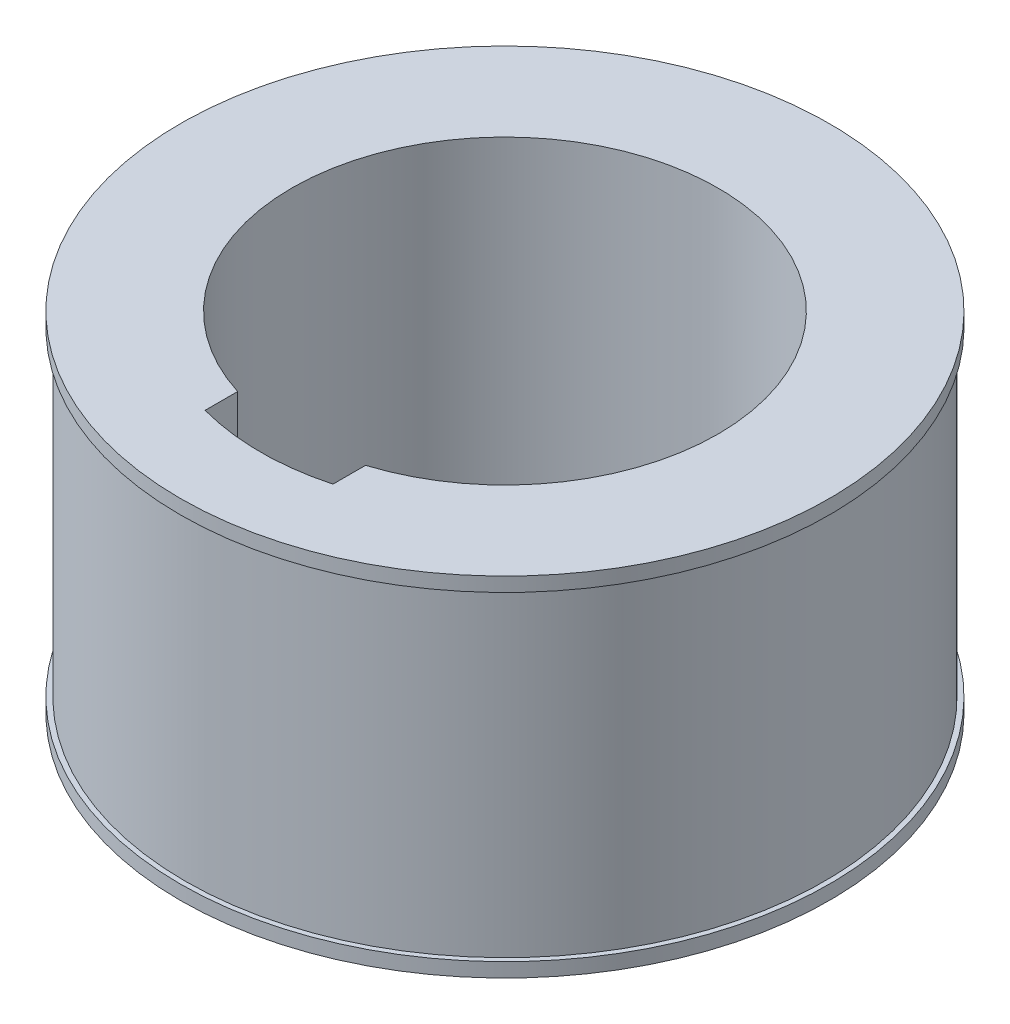
SolidWorks part; units mm, degrees
ref_plane "Front Plane" through (0, 0, 0) normal (0, 0, 1) x (1, 0, 0)
ref_plane "Top Plane" through (0, 0, 0) normal (0, 1, 0) x (1, 0, 0)
ref_plane "Right Plane" through (0, 0, 0) normal (1, 0, 0) x (0, 0, -1)
sketch "Sketch1" plane through (0, 0, 0) normal (0, 1, 0) x (1, 0, 0)
  circle A0 centre (0, 0) radius 45
  dimension "D1" = 90
extrude "Boss-Extrude1" add sketch "Sketch1" along normal mid plane 45
sketch "Sketch2" plane through (0, 22.5, 0) normal (0, 1, 0) x (1, 0, 0)
  circle A2 centre (0, 0) radius 45.69
  circle A3 centre (0, 0) radius 45.69
  dimension "D1" = 0.69
extrude "Boss-Extrude2" add sketch "Sketch2" along normal blind 2
mirror "Mirror1" about plane through (0, 0, 0) normal (0, 1, 0) of "Boss-Extrude2"
sketch "Sketch3" plane through (0, 0, 0) normal (0, 1, 0) x (1, 0, 0)
  circle A0 centre (0, 0) radius 40
  circle A1 centre (0, 0) radius 38
  point P3 (0, 0)
  dimension "D1" = 80
  dimension "D2" = 2
extrude "Cut-Extrude1" cut sketch "Sketch3" against normal blind 32
sketch "Sketch4" plane through (0, -24.5, 0) normal (0, -1, 0) x (1, 0, 0)
  circle A0 centre (0, 0) radius 30
  dimension "D1" = 60
extrude "Cut-Extrude2" cut sketch "Sketch4" against normal through all
sketch "Sketch6" plane through (0, -24.5, 0) normal (0, -1, 0) x (1, 0, 0)
  line L1 (-9, 28.6182) -> (-9, 33.2018)
  line L2 (9, 28.6182) -> (9, 33.2018)
  circle A2 centre (0, 0) radius 30 construction
  circle A3 centre (0, 0) radius 34.4
  arc A4 (9, 33.2018) -> (-9, 33.2018) centre (0, 0) ccw
  arc A5 (9, 28.6182) -> (-9, 28.6182) centre (0, 0) ccw
  dimension "D2" = 4.4
extrude "Cut-Extrude3" cut sketch "Sketch6" against normal through all
